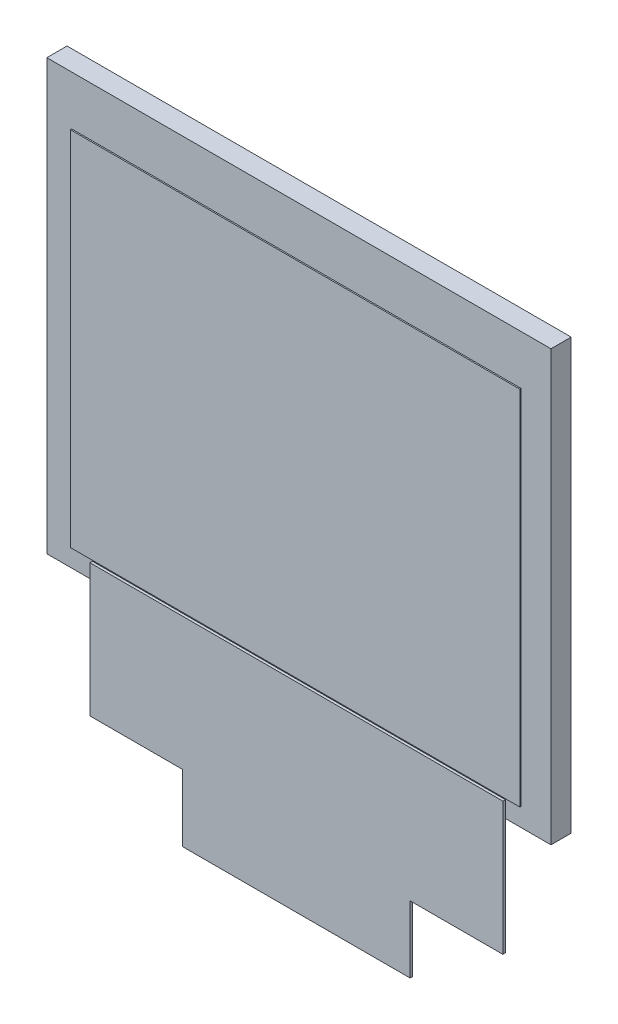
SolidWorks part; units mm, degrees
ref_plane "前视基准面" through (0, 0, 0) normal (0, 0, 1) x (1, 0, 0)
ref_plane "上视基准面" through (0, 0, 0) normal (0, 1, 0) x (1, 0, 0)
ref_plane "右视基准面" through (0, 0, 0) normal (1, 0, 0) x (0, 0, -1)
sketch "草图1" plane through (0, 0, 0) normal (0, 0, 1) x (1, 0, 0)
  line L0 (-31.8674, 0) -> (28.7375, 0) construction
  line L1 (-19.95, 17) -> (19.95, 17)
  line L2 (-19.95, 17) -> (-19.95, -17)
  line L3 (-19.95, -17) -> (19.95, -17)
  line L4 (19.95, 17) -> (19.95, -17)
  line L5 (0, -21.6346) -> (0, 24.0522) construction
  dimension "D1" = 39.9
  dimension "D2" = 34
extrude "凸台-拉伸1" add sketch "草图1" along normal blind 1.6
sketch "草图2" plane through (0, 0, 1.6) normal (0, 0, 1) x (1, 0, 0)
  line L0 (0, 16.2915) -> (0, -17.1684) construction
  line L1 (-16.34, -15.7079) -> (16.34, -15.7079)
  line L2 (-16.34, -15.7079) -> (-16.34, -26.2079)
  line L3 (-16.34, -26.2079) -> (-9, -26.2079)
  line L4 (16.34, -15.7079) -> (16.34, -26.2079)
  line L5 (-9, -26.2079) -> (-9, -31.5)
  line L6 (-9, -31.5) -> (9, -31.5)
  line L7 (9, -31.5) -> (9, -26.2079)
  line L8 (9, -26.2079) -> (16.34, -26.2079)
  line L9 (-19.95, -17) -> (19.95, -17) construction
  dimension "D1" = 32.68
  dimension "D2" = 10.5
  dimension "D3" = 14.5
  dimension "D4" = 18
extrude "凸台-拉伸2" add sketch "草图2" along normal blind 0.2
sketch "草图3" plane through (0, 0, 1.8) normal (0, 0, 1) x (1, 0, 0)
  line L0 (0, 15.6169) -> (0, -16.6962) construction
  line L1 (-17.7875, 13.3) -> (17.7875, 13.3)
  line L2 (-17.7875, 13.3) -> (-17.7875, -15.34)
  line L3 (-17.7875, -15.34) -> (17.7875, -15.34)
  line L4 (17.7875, 13.3) -> (17.7875, -15.34)
  line L6 (19.95, 17) -> (-19.95, 17) construction
  dimension "D1" = 28.64
  dimension "D2" = 35.575
  dimension "D3" = 3.7
extrude "凸台-拉伸3" add sketch "草图3" along normal blind 0.1
